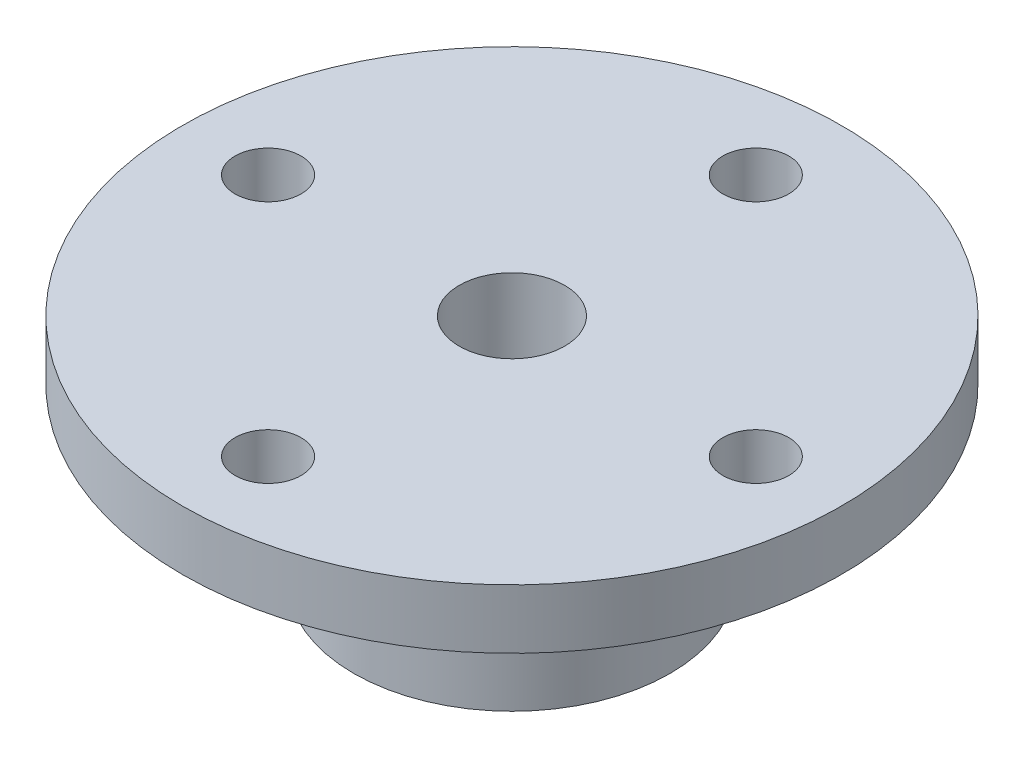
SolidWorks part; units mm, degrees
ref_plane "前视基准面" through (0, 0, 0) normal (0, 0, 1) x (1, 0, 0)
ref_plane "上视基准面" through (0, 0, 0) normal (0, 1, 0) x (1, 0, 0)
ref_plane "右视基准面" through (0, 0, 0) normal (1, 0, 0) x (0, 0, -1)
other "Configuration Table"
sketch "草图1" plane through (0, 0, 0) normal (0, 1, 0) x (1, 0, 0)
  circle A0 centre (0, 0) radius 12
  circle A1 centre (0, 0) radius 4
  dimension "D1" = 8
  dimension "D2" = 24
extrude "凸台-拉伸1" add sketch "草图1" along normal blind 13
sketch "草图2" plane through (0, 13, 0) normal (0, 1, 0) x (1, 0, 0)
  circle A0 centre (0, 0) radius 25
  circle A1 centre (0, 0) radius 4
  circle A2 centre (0, 0) radius 18.5
  circle A3 centre (0, 18.5) radius 2.5
  circle A4 centre (-18.5, 0) radius 2.5
  circle A5 centre (18.5, 0) radius 2.5
  circle A6 centre (0, -18.5) radius 2.5
  circle M1 centre (0, 0) radius 12
  circle M2 centre (0, 0) radius 4
  dimension "D1" = 8
  dimension "D2" = 50
  dimension "D3" = 37
  dimension "D4" = 5
  dimension "D5" = 5
  dimension "D6" = 5
  dimension "D7" = 5
extrude "凸台-拉伸2" add sketch "草图2" along normal blind 4.5 contours A0 A6 A2 A4 A3 A5 | A6 A2 A5 A3 A4 M1 | M1 M2
